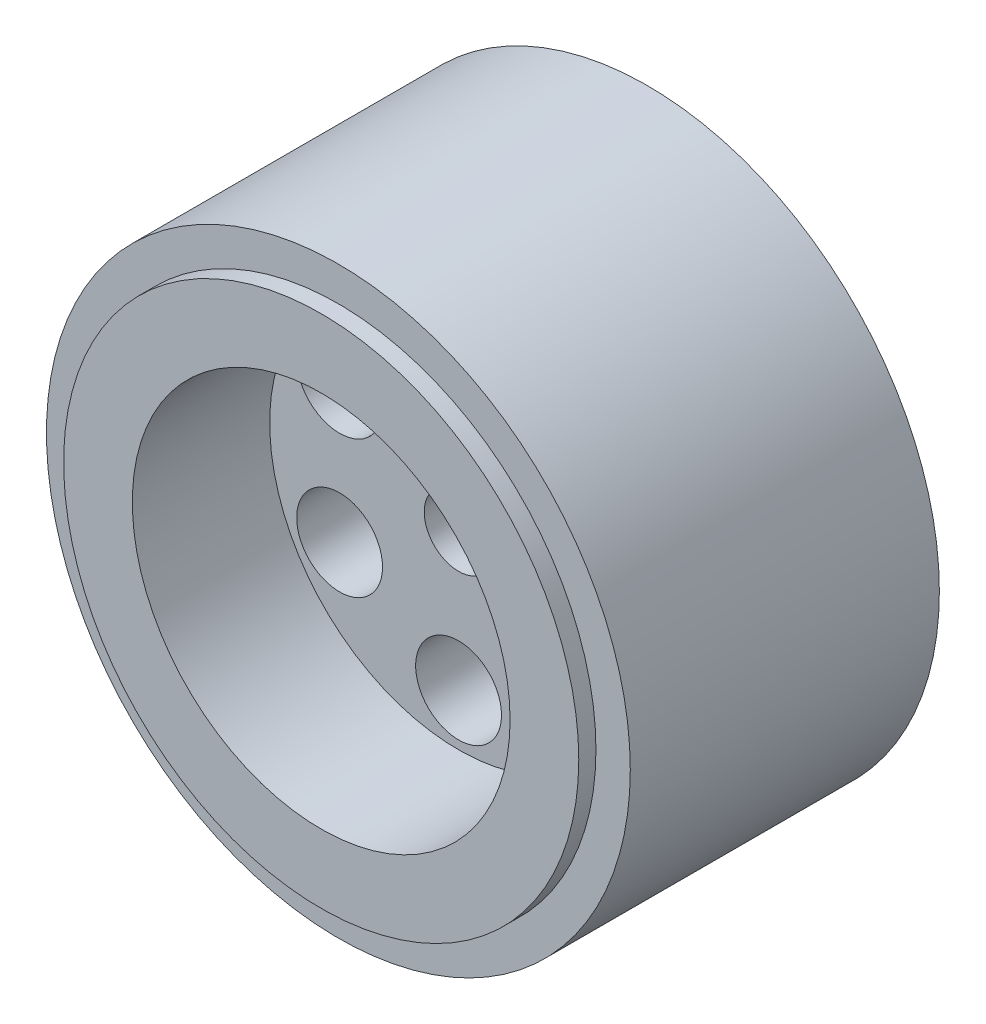
SolidWorks part; units mm, degrees
ref_plane "Front Plane" through (0, 0, 0) normal (0, 0, 1) x (1, 0, 0)
ref_plane "Top Plane" through (0, 0, 0) normal (0, 1, 0) x (1, 0, 0)
ref_plane "Right Plane" through (0, 0, 0) normal (1, 0, 0) x (0, 0, -1)
sketch "Sketch1" plane through (0, 0, 0) normal (1, 0, 0) x (0, 0, -1)
  line L0 (0, 0) -> (141.0669, 0) construction
  line L1 (0, 4) -> (0, 22)
  line L2 (0, 22) -> (-14, 22)
  line L3 (-16, 22) -> (-16, 30)
  line L4 (-16, 30) -> (-14, 30)
  line L5 (-14, 30) -> (-14, 28)
  line L8 (22, 22) -> (8, 22)
  line L9 (8, 22) -> (8, 10)
  line L10 (8, 10) -> (22, 10)
  line L11 (24, 10) -> (24, 4) construction
  line L12 (22, 4) -> (0, 4)
  line L13 (-14, 36) -> (22, 36) construction
  line L15 (-14, 28) -> (22, 28)
  line L16 (22, 28) -> (22, 30) construction
  line L17 (22, 30) -> (24, 30) construction
  line L19 (-14, 28) -> (-14, 22) construction
  line L20 (22, 28) -> (22, 22)
  line L21 (22, 10) -> (22, 4)
  line L22 (-16, 22) -> (-14, 22)
  line L23 (22, 22) -> (24, 22) construction
  line L24 (22, 10) -> (24, 10) construction
  line L25 (22, 4) -> (24, 4) construction
  line L26 (22, 28) -> (24, 28) construction
  line L27 (24, 30) -> (24, 28) construction
  line L28 (24, 22) -> (24, 28) construction
  dimension "D1" = 4
  dimension "D2" = 36
  dimension "D3" = 2
  dimension "D4" = 2
  dimension "D5" = 6
  dimension "D6" = 14
  dimension "D7" = 8
  dimension "D8" = 10
  dimension "D9" = 36
  dimension "D10" = 8
  dimension "D11" = 36
revolve "Revolve1" add sketch "Sketch1" angle 360 about L0
sketch "Sketch2" plane through (0, 0, 0) normal (0, 0, 1) x (1, 0, 0)
  line L0 (0, 16) -> (0, 0) construction
  circle A0 centre (0, 16) radius 5
  circle A1 centre (13.8564, 8) radius 5
  circle A2 centre (13.8564, -8) radius 5
  circle A3 centre (0, -16) radius 5
  circle A4 centre (-13.8564, -8) radius 5
  circle A5 centre (-13.8564, 8) radius 5
  point P16 (0, 0)
  dimension "D1" = 10
  dimension "D2" = 16
extrude "Cut-Extrude1" cut sketch "Sketch2" against normal up to surface (8 mm away) up to face at (22, 0, -8)
sketch "Sketch3" plane through (0, 0, 0) normal (1, 0, 0) x (0, 0, -1)
  line L0 (21.999, 34.001) -> (-13.999, 34.001)
  line L1 (-13.999, 34.001) -> (-13.999, 28.001)
  line L2 (-13.999, 28.001) -> (21.999, 28.001)
  line L3 (21.999, 28.001) -> (21.999, 34.001)
  line L4 (22, 28) -> (-14, 28) construction
  line L5 (22, 28) -> (-14, 28) construction
  line L7 (0, 0) -> (22, 0) construction
  line L9 (22, -28) -> (22, 28) construction
  dimension "D1" = 0.001
  dimension "D2" = 0.001
  dimension "D3" = 0.001
  dimension "D4" = 6
revolve "Revolve2" add sketch "Sketch3" angle 360 about L7
